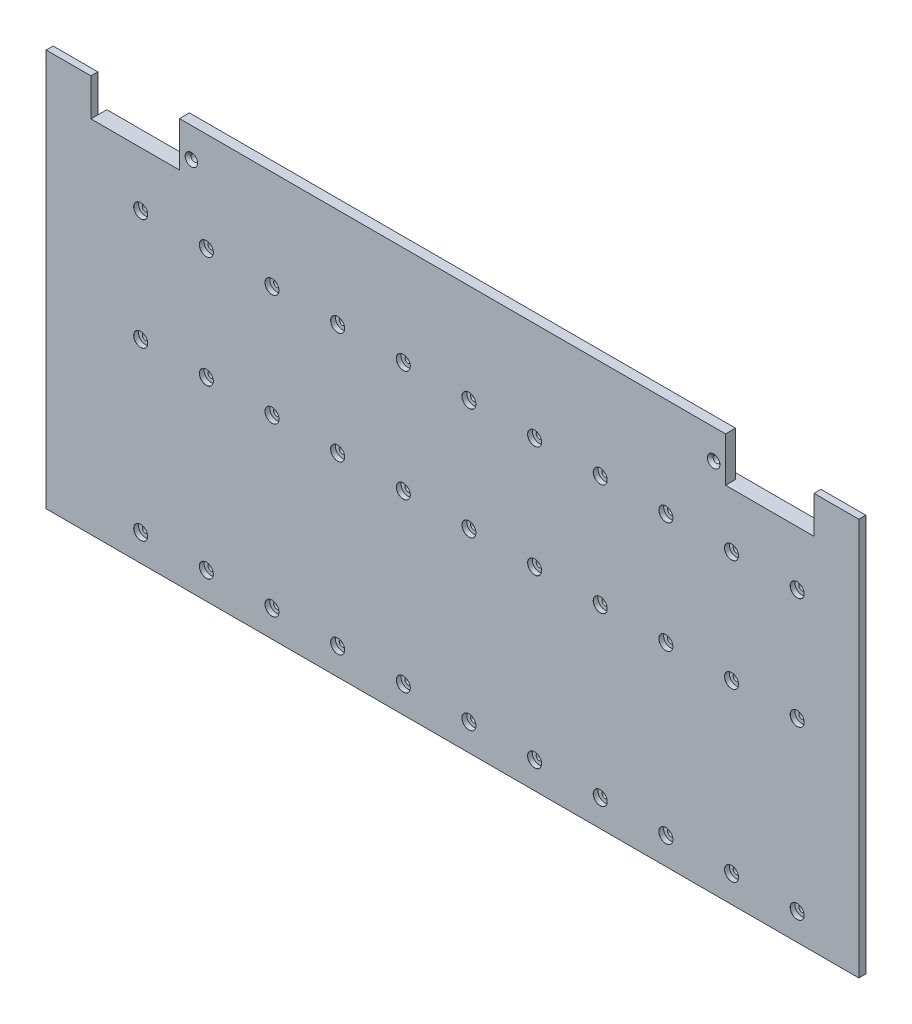
SolidWorks part; units mm, degrees
ref_plane "Plan de face" through (0, 0, 0) normal (0, 0, 1) x (1, 0, 0)
ref_plane "Plan de dessus" through (0, 0, 0) normal (0, 1, 0) x (1, 0, 0)
ref_plane "Plan de droite" through (0, 0, 0) normal (1, 0, 0) x (0, 0, -1)
sketch "Esquisse1" plane through (0, 0, 0) normal (0, 0, 1) x (1, 0, 0)
  line L1 (-204.25, -90.5) -> (204.25, -90.5)
  line L2 (-204.25, -90.5) -> (-204.25, 90.5)
  line L3 (-204.25, 90.5) -> (204.25, 90.5)
  line L4 (204.25, -90.5) -> (204.25, 90.5)
  line L5 (-204.25, -90.5) -> (204.25, 90.5) construction
  line L6 (-204.25, 90.5) -> (204.25, -90.5) construction
  point P0 (0, 0)
  dimension "D1" = 181
  dimension "D2" = 408.5
extrude "Boss.-Extru.1" add sketch "Esquisse1" along normal blind 8 contours L3 L4 L1 L2
hole_wizard "Chambrage pour vis à tête ronde bombée M31" positions "Esquisse2" profile "Esquisse3" counterbore size "M3" standard "Ansi Metric" end condition through all
sketch "Esquisse2" plane through (0, 0, 8) normal (0, 0, 1) x (1, 0, 0)
  point P0 (-156.75, 63)
  point P3 (-156.75, 7)
  point P6 (-156.75, -77)
sketch "Esquisse3" plane through (-156.75, 63, 8) normal (1, 0, 0) x (0, -1, 0)
  line L0 (0, 0) -> (0, 8)
  line L1 (0, 8) -> (1.6, 8)
  line L3 (1.6, 8) -> (1.6, 2.4)
  line L4 (3.5, 2.4) -> (1.6, 2.4)
  line L5 (3.5, 2.4) -> (3.5, 0.025)
  line L6 (3.5, 0.025) -> (3.525, 0)
  line L7 (3.525, 0) -> (0, 0)
  line L8 (-3.5, 0.025) -> (-3.525, 0) construction
  line L11 (0, -6.35) -> (0, 107.95) construction
  dimension "Diamètre du perçage jusqu'au prochain" = 3.2
  dimension "Profondeur du perçage jusqu'au prochain" = 8
  dimension "Diamètre du chambrage" = 7
  dimension "Profondeur du chambrage" = 2.4
  dimension "Diamètre du fraisage entrant" = 7.05
  dimension "Angle du fraisage entrant" = 90
pattern_linear "Répétition linéaire1" count 11 spacing 33 along (1, 0, 0) of "Chambrage pour vis à tête ronde bombée M31"
sketch "Esquisse4" plane through (0, 90.5, 0) normal (0, 1, 0) x (1, 0, 0)
  line L0 (-204.25, 0) -> (204.25, 0) construction
  line L1 (-204.25, 0) -> (-181.75, 0)
  line L2 (-204.25, 0) -> (-204.25, -4.5)
  line L3 (-204.25, -4.5) -> (-181.75, -4.5)
  line L4 (-181.75, 0) -> (-181.75, -4.5)
  line L5 (-204.25, -8) -> (204.25, -8) construction
  line L7 (0, -4.4) -> (0, 4.4) construction
  line L8 (181.75, 0) -> (181.75, -4.5)
  line L9 (204.25, -4.5) -> (181.75, -4.5)
  line L10 (204.25, 0) -> (204.25, -4.5)
  line L11 (204.25, 0) -> (181.75, 0)
  line L12 (-204.25, -8) -> (-204.25, 0) construction
  dimension "D1" = 3.5
  dimension "D3" = 22.5
extrude "Enlèv. mat.-Extru.1" cut sketch "Esquisse4" against normal up to surface (181 mm away) up to face at (0, -90.5, 4)
sketch "Esquisse5" plane through (0, 0, 8) normal (0, 0, 1) x (1, 0, 0)
  line L1 (-204.25, 90.5) -> (-181.75, 90.5)
  line L2 (-204.25, 90.5) -> (-204.25, 109.225)
  line L3 (-204.25, 109.225) -> (-181.75, 109.225)
  line L4 (-181.75, 90.5) -> (-181.75, 109.225)
  line L6 (-204.25, 90.5) -> (204.25, 90.5) construction
  dimension "D1" = 22.5
  dimension "D2" = 18.725
extrude "Boss.-Extru.2" add sketch "Esquisse5" against normal up to surface (3.5 mm away) up to face at (-193, 0, 4.5)
mirror "Symétrie1" about plane through (0, 0, 0) normal (1, 0, 0) of "Boss.-Extru.2"
sketch "Esquisse7" plane through (0, 0, 8) normal (0, 0, 1) x (1, 0, 0)
  line L0 (-181.75, 90.5) -> (181.75, 90.5) construction
  line L1 (-137.25, 90.5) -> (137.25, 90.5)
  line L2 (-137.25, 90.5) -> (-137.25, 112.875)
  line L3 (-137.25, 112.875) -> (137.25, 112.875)
  line L4 (137.25, 90.5) -> (137.25, 112.875)
  line L5 (137.75, 91) -> (137.75, 116.55) construction
  line L6 (-137.75, 91) -> (-137.75, 116.55) construction
  line L7 (-124.75, 113.375) -> (-137.75, 113.375) construction
  dimension "D1" = 0.5
  dimension "D2" = 0.5
  dimension "D3" = 0.5
extrude "Boss.-Extru.3" add sketch "Esquisse7" against normal blind 5
hole_wizard "Fraisage pour vis à tête fraisée M31" positions "Esquisse8" profile "Esquisse9" countersink size "M3" standard "Ansi Metric" end condition through all
sketch "Esquisse8" plane through (0, 0, 8) normal (0, 0, 1) x (1, 0, 0)
  point P0 (-131.25, 98)
  point P3 (131.25, 98)
sketch "Esquisse9" plane through (-131.25, 98, 8) normal (1, 0, 0) x (0, -1, 0)
  line L0 (0, 0) -> (0, 8)
  line L1 (0, 8) -> (1.7, 8)
  line L2 (1.7, 8) -> (1.7, 1.45)
  line L3 (1.7, 1.45) -> (3.15, 0)
  line L5 (3.15, 0) -> (0, 0)
  line L6 (-1.7, 1.45) -> (-3.15, 0) construction
  line L11 (0, -6.35) -> (0, 107.95) construction
  dimension "Diamètre du perçage jusqu'au prochain" = 3.4
  dimension "Profondeur du perçage jusqu'au prochain" = 8
  dimension "Diamètre du fraisage entrant" = 6.3
  dimension "Angle du fraisage entrant" = 90
